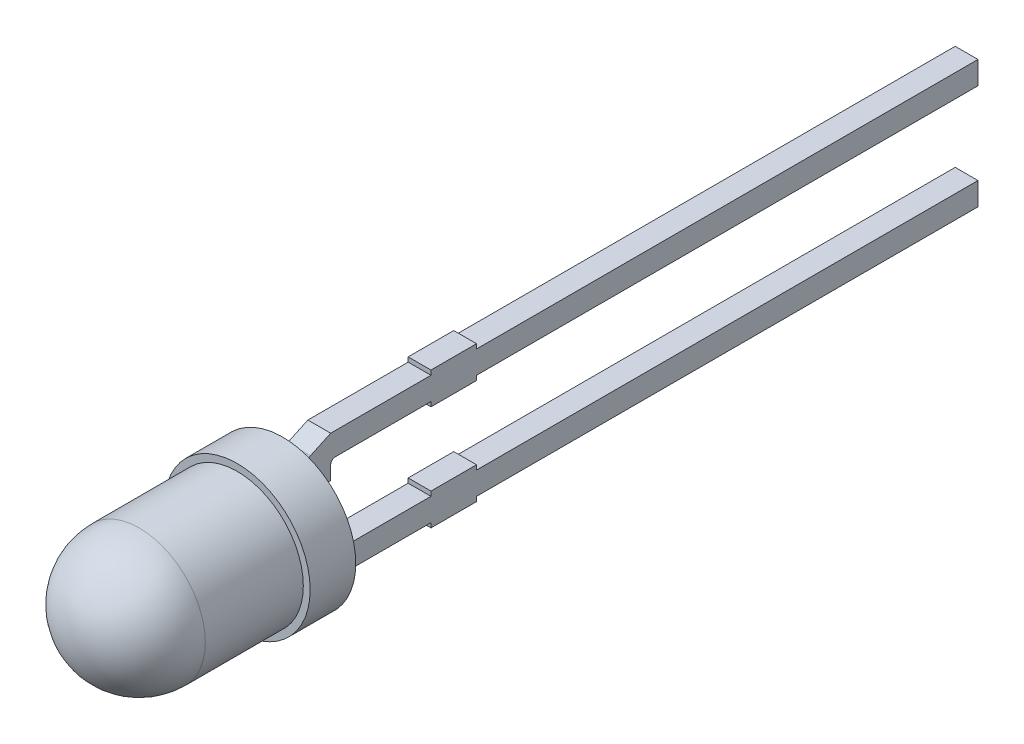
SolidWorks part; units mm, degrees
ref_plane "Front" through (0, 0, 0) normal (0, 0, 1) x (1, 0, 0)
ref_plane "Top" through (0, 0, 0) normal (0, 1, 0) x (1, 0, 0)
ref_plane "Right" through (0, 0, 0) normal (1, 0, 0) x (0, 0, -1)
sketch "Sketch1" plane through (0, 0, 0) normal (1, 0, 0) x (0, 0, -1)
  line L0 (0, 0) -> (76.2974, 0) construction
  line L1 (0, 1.45) -> (2.15, 1.45)
  line L2 (2.15, 1.45) -> (2.15, 1.6)
  line L3 (2.15, 1.6) -> (3.15, 1.6)
  line L4 (3.15, 1.6) -> (3.15, 0)
  line L5 (3.15, 0) -> (-1.45, 0)
  arc A0 (0, 1.45) -> (-1.45, 0) centre (0, 0) ccw
  dimension "D1" = 1.45
  dimension "D2" = 4.6
  dimension "D3" = 1
  dimension "D4" = 1.6
revolve "Revolve1" add sketch "Sketch1" angle 360 about L0
sketch "Sketch2" plane through (0, 0, 0) normal (1, 0, 0) x (0, 0, -1)
  line L0 (3.15, -1.6) -> (3.15, 1.6) construction
  line L1 (3.15, -1.6) -> (3.15, 1.6) construction
  line L2 (3.15, 1.027) -> (3.95, 1.4)
  line L3 (3.95, 1.4) -> (6.15, 1.4)
  line L4 (6.15, 1.4) -> (6.15, 1.5)
  line L5 (6.15, 1.5) -> (7.15, 1.5)
  line L6 (7.15, 1.5) -> (7.15, 1.4)
  line L7 (7.15, 1.4) -> (30.15, 1.4)
  line L8 (30.15, 1.4) -> (30.15, 0.9)
  line L9 (30.15, 0.9) -> (7.15, 0.9)
  line L10 (7.15, 0.9) -> (7.15, 0.8)
  line L11 (7.15, 0.8) -> (6.15, 0.8)
  line L12 (6.15, 0.8) -> (6.15, 0.9)
  line L13 (6.15, 0.9) -> (4.05, 0.9)
  line L14 (3.95, 0.8) -> (3.95, 0.5)
  line L15 (3.95, 0.5) -> (3.15, 0.5)
  line L16 (3.15, 0) -> (7.9733, 0) construction
  line L17 (3.15, 1.027) -> (3.15, 0.5)
  line L18 (3.95, -0.8) -> (3.95, -0.5)
  line L19 (6.15, -0.9) -> (4.05, -0.9)
  line L20 (6.15, -0.8) -> (6.15, -0.9)
  line L21 (7.15, -0.8) -> (6.15, -0.8)
  line L22 (7.15, -0.9) -> (7.15, -0.8)
  line L23 (30.15, -0.9) -> (7.15, -0.9)
  line L24 (30.15, -1.4) -> (30.15, -0.9)
  line L25 (7.15, -1.4) -> (30.15, -1.4)
  line L26 (7.15, -1.5) -> (7.15, -1.4)
  line L27 (6.15, -1.5) -> (7.15, -1.5)
  line L28 (6.15, -1.4) -> (6.15, -1.5)
  line L29 (3.95, -1.4) -> (6.15, -1.4)
  line L30 (3.15, -1.027) -> (3.95, -1.4)
  line L31 (3.15, -1.027) -> (3.15, -0.5)
  line L32 (3.95, -0.5) -> (3.15, -0.5)
  arc A0 (4.05, 0.9) -> (3.95, 0.8) centre (4.05, 0.8) ccw
  arc A1 (4.05, -0.9) -> (3.95, -0.8) centre (4.05, -0.8) cw
  point P19 (3.15, 0)
  dimension "D1" = 0.5
  dimension "D2" = 0.7
  dimension "D3" = 1.4
  dimension "D4" = 0.8
  dimension "D5" = 27
  dimension "D6" = 115
  dimension "D7" = 4
  dimension "D8" = 1
  dimension "D9" = 0.5
  dimension "D10" = 0.1
extrude "Extrude1" add sketch "Sketch2" along normal mid plane 0.5
fillet "Fillet1" radius 0.25 8 edges at (0, -0.5, -3.15) (0, -1.027, -3.15) (-0.25, -0.7635, -3.15) (0, 0.5, -3.15) (-0.25, 0.7635, -3.15) (0, 1.027, -3.15) (0.25, 0.7635, -3.15) (0.25, -0.7635, -3.15)
sketch "Sketch3" plane through (0, 0, 0) normal (1, 0, 0) x (0, 0, -1)
  line L0 (7.15, -1.4) -> (30.15, -1.4) construction
  line L1 (30.15, 1.4) -> (18.15, 1.4)
  line L2 (30.15, 1.4) -> (30.15, -1.4)
  line L3 (30.15, -1.4) -> (18.15, -1.4)
  line L4 (18.15, 1.4) -> (18.15, -1.4)
  dimension "D1" = 15
extrude "Cut-Extrude1" cut sketch "Sketch3" against normal through all both and the other way through all
